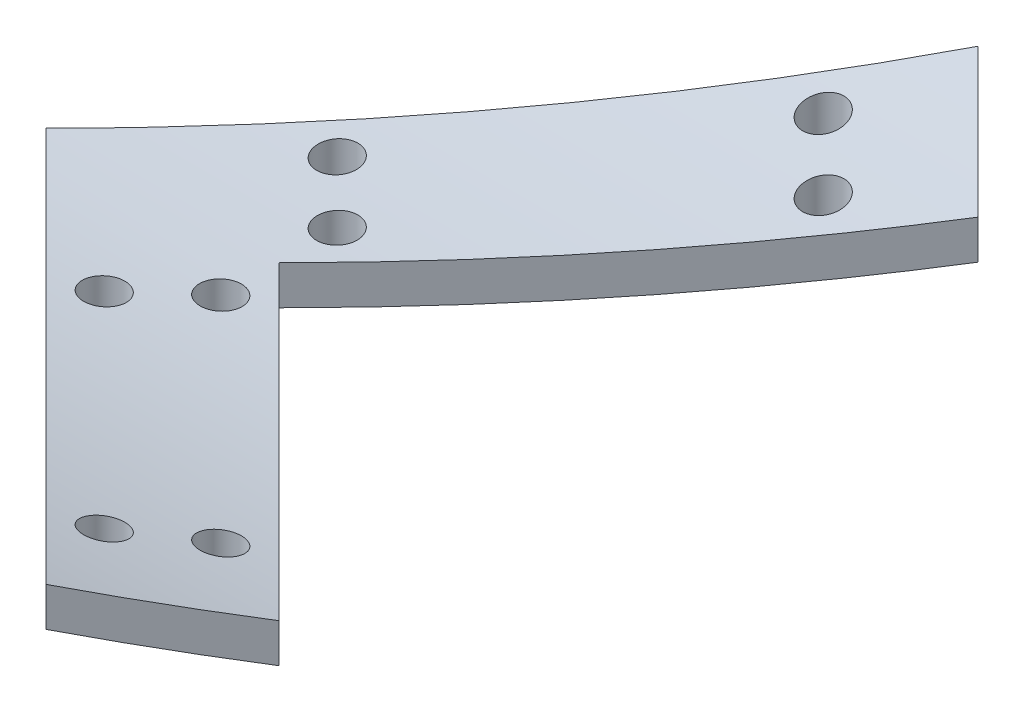
SolidWorks part; units mm, degrees
ref_plane "Front Plane" through (0, 0, 0) normal (0, 0, 1) x (1, 0, 0)
ref_plane "Top Plane" through (0, 0, 0) normal (0, 1, 0) x (1, 0, 0)
ref_plane "Right Plane" through (0, 0, 0) normal (1, 0, 0) x (0, 0, -1)
sketch "Sketch3" plane through (0, 0, 0) normal (1, 0, 0) x (0, 0, -1)
  line L0 (-8.3933, 1.9614) -> (-8.3933, -4.052)
  line L6 (-8.3933, -4.3886) -> (-8.3933, 1.9614)
  line L8 (232.9067, -4.3886) -> (232.9067, 1.9614)
  line L9 (232.9067, -4.052) -> (232.9067, 1.9614)
  arc A2 (-8.3933, 1.9614) -> (232.9067, 1.9614) centre (112.2567, 210.9333) ccw
  arc A3 (-8.3933, -4.052) -> (232.9067, -4.052) centre (112.2567, 204.9199) ccw
  dimension "D1" = 6.35
  dimension "D2" = 241.3
extrude "Boss-Extrude4" add sketch "Sketch3" along normal blind 304.8 contours L0 A3 L8 A2
ref_plane "Plane1" through (0, 1.9614, 0) normal (0, 1, 0) x (1, 0, 0)
sketch "Sketch4" plane through (0, 1.9614, 0) normal (0, 1, 0) x (1, 0, 0)
  line L0 (105.3563, 184.0987) -> (33.5143, 112.2567)
  line L1 (105.3563, 184.0987) -> (123.3169, 166.1382)
  line L2 (123.3169, 166.1382) -> (69.4353, 112.2567)
  line L18 (123.3168, 58.3752) -> (105.3563, 40.4147)
  line L19 (105.3563, 40.4147) -> (33.5143, 112.2567)
  line L20 (123.3168, 58.3752) -> (69.4353, 112.2567)
  point P19 (50.8, 172.5817)
extrude "Cut-Extrude2" cut sketch "Sketch4" against normal blind 150 flip side to cut
sketch "Sketch6" plane through (0, 1.9614, 0) normal (0, 1, 0) x (1, 0, 0)
  line L11 (69.4353, 112.2567) -> (33.5143, 112.2567)
  circle A0 centre (97.9168, 167.679) radius 3.175
  circle A1 centre (106.8971, 158.6987) radius 3.175
  circle A2 centre (60.4551, 130.2173) radius 3.175
  circle A3 centre (69.4353, 121.237) radius 3.175
  circle A6 centre (60.455, 94.2962) radius 3.175
  circle A7 centre (69.4353, 103.2764) radius 3.175
  circle A8 centre (106.897, 65.8146) radius 3.175
  circle A9 centre (97.9167, 56.8344) radius 3.175
extrude "Cut-Extrude5" cut sketch "Sketch6" against normal blind 150 contours A1 | A0 | A2 | A3 | A7 | A6 | A9 | A8
